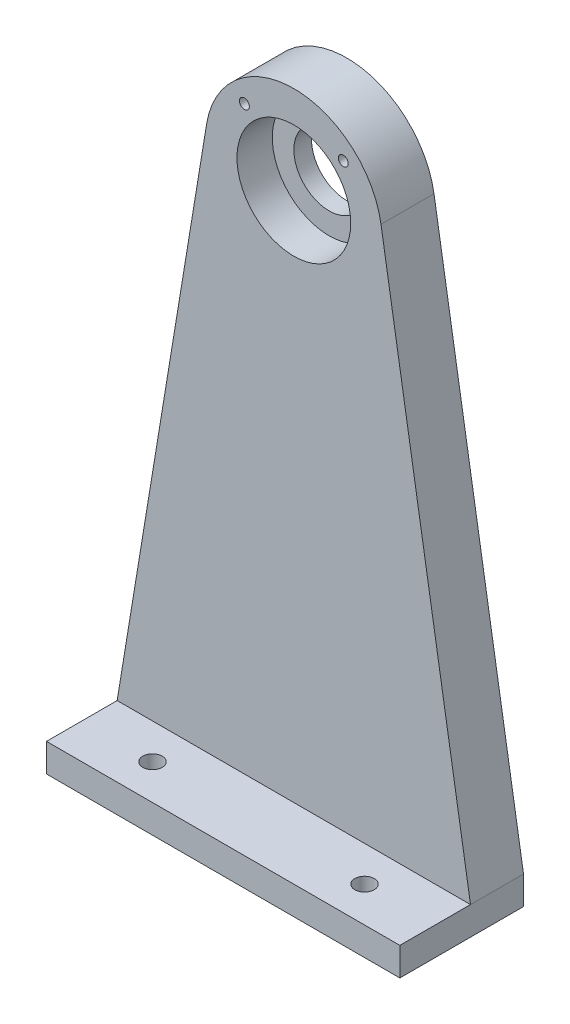
SolidWorks part; units mm, degrees
material "PEI"
ref_plane "Front Plane" through (0, 0, 0) normal (0, 0, 1) x (1, 0, 0)
ref_plane "Top Plane" through (0, 0, 0) normal (0, 1, 0) x (1, 0, 0)
ref_plane "Right Plane" through (0, 0, 0) normal (1, 0, 0) x (0, 0, -1)
sketch "Sketch1" plane through (0, 0, 0) normal (0, 0, 1) x (1, 0, 0)
  line L0 (0, 0) -> (0, -150) construction
  line L5 (24.6687, 4.0562) -> (50, -150)
  line L6 (50, -150) -> (-50, -150)
  line L7 (-50, -150) -> (-24.6687, 4.0562)
  arc A1 (24.6687, 4.0562) -> (-24.6687, 4.0562) centre (0, 0) ccw
  point P19 (0, -150)
  dimension "D2" = 50
  dimension "D3" = 150
  dimension "D4" = 100
extrude "Boss-Extrude1" add sketch "Sketch1" along normal mid plane 15
sketch "Sketch7" plane through (0, -150, 0) normal (0, -1, 0) x (1, 0, 0)
  line L0 (50, 7.5) -> (50, -7.5) construction
  line L1 (-50, -7.5) -> (50, -7.5)
  line L2 (-50, -7.5) -> (-50, 27.5)
  line L3 (-50, 27.5) -> (50, 27.5)
  line L4 (50, -7.5) -> (50, 27.5)
  line L5 (-50, -7.5) -> (50, 27.5) construction
  line L6 (-50, 27.5) -> (50, -7.5) construction
  line L7 (-50, -7.5) -> (50, -7.5) construction
  line L9 (-50, 7.5) -> (-50, -7.5) construction
  point P4 (0, 10)
  dimension "D1" = 35
extrude "Boss-Extrude2" add sketch "Sketch7" along normal blind 8
sketch "Sketch5" plane through (0, 0, 7.5) normal (0, 0, 1) x (1, 0, 0)
  circle A0 centre (0, 0) radius 16.1
  dimension "D1" = 32.2
extrude "Cut-Extrude1" cut sketch "Sketch5" against normal blind 10
sketch "Sketch6" plane through (0, 0, -2.5) normal (0, 0, 1) x (1, 0, 0)
  circle A0 centre (0, 0) radius 10
  dimension "D1" = 20
extrude "Cut-Extrude2" cut sketch "Sketch6" against normal blind 20
hole_wizard "M5 Clearance Hole1" positions "Sketch9" profile "Sketch10" hole size "M5" standard "ANSI Metric"
sketch "Sketch9" plane through (0, -150, 0) normal (0, 1, 0) x (1, 0, 0)
  line L0 (50, -27.5) -> (-50, -27.5) construction
  point P0 (-30, -17.5)
  dimension "D1" = 30
  dimension "D2" = 10
sketch "Sketch10" plane through (-30, -150, 17.5) normal (1, 0, 0) x (0, 0, 1)
  line L0 (0, 0) -> (0, 11.6524)
  line L1 (0, 11.6524) -> (2.75, 10)
  line L2 (2.75, 10) -> (2.75, 0)
  line L5 (2.75, 0) -> (0, 0)
  line L10 (0, 11.6524) -> (-2.75, 10) construction
  line L11 (0, -6.35) -> (0, 107.95) construction
  dimension "Hole Dia." = 5.5
  dimension "Hole Depth" = 10
  dimension "Drill Angle" = 118
mirror "Mirror1" about plane through (0, 0, 0) normal (1, 0, 0) of "M5 Clearance Hole1"
sketch "Sketch11" plane through (0, 0, 7.5) normal (0, 0, 1) x (1, 0, 0)
  circle A0 centre (0, 0) radius 20 construction
  circle A1 centre (14, 14.2829) radius 1.4
  circle A5 centre (-14, 14.2829) radius 1.4
  point P14 (0, 0)
  dimension "D1" = 40
  dimension "D2" = 2.8
  dimension "D3" = 14
extrude "Cut-Extrude3" cut sketch "Sketch11" against normal blind 8
sketch "Sketch12" plane through (0, 0, -7.5) normal (0, 0, -1) x (-1, 0, 0)
  circle A0 centre (9, -50) radius 1.4
  circle A1 centre (-9, -50) radius 1.4
  dimension "D1" = 2.8
  dimension "D2" = 18
  dimension "D3" = 50
  dimension "D4" = 9
extrude "Cut-Extrude4" cut sketch "Sketch12" against normal blind 8
equation "\"SupportLength\"= 15cm"
equation "\"trail\"= 10cm"
equation "\"D4@Sketch1\"=\"trail\""
equation "\"D3@Sketch1\"=\"SupportLength\""
equation "\"curve\"= 5cm"
equation "\"holesDist\"= 8cm"
equation "\"BearingWidth\"= 1cm"
equation "\"BearingOD\"= 3.22cm"
equation "\"BearingBore\"= 1cm"
equation "\"D1@Sketch5\"=\"BearingOD\""
equation "\"D1@Cut-Extrude1\"=\"BearingWidth\""
equation "\"D1@Sketch6\"=\"BearingBore\" + 1"
